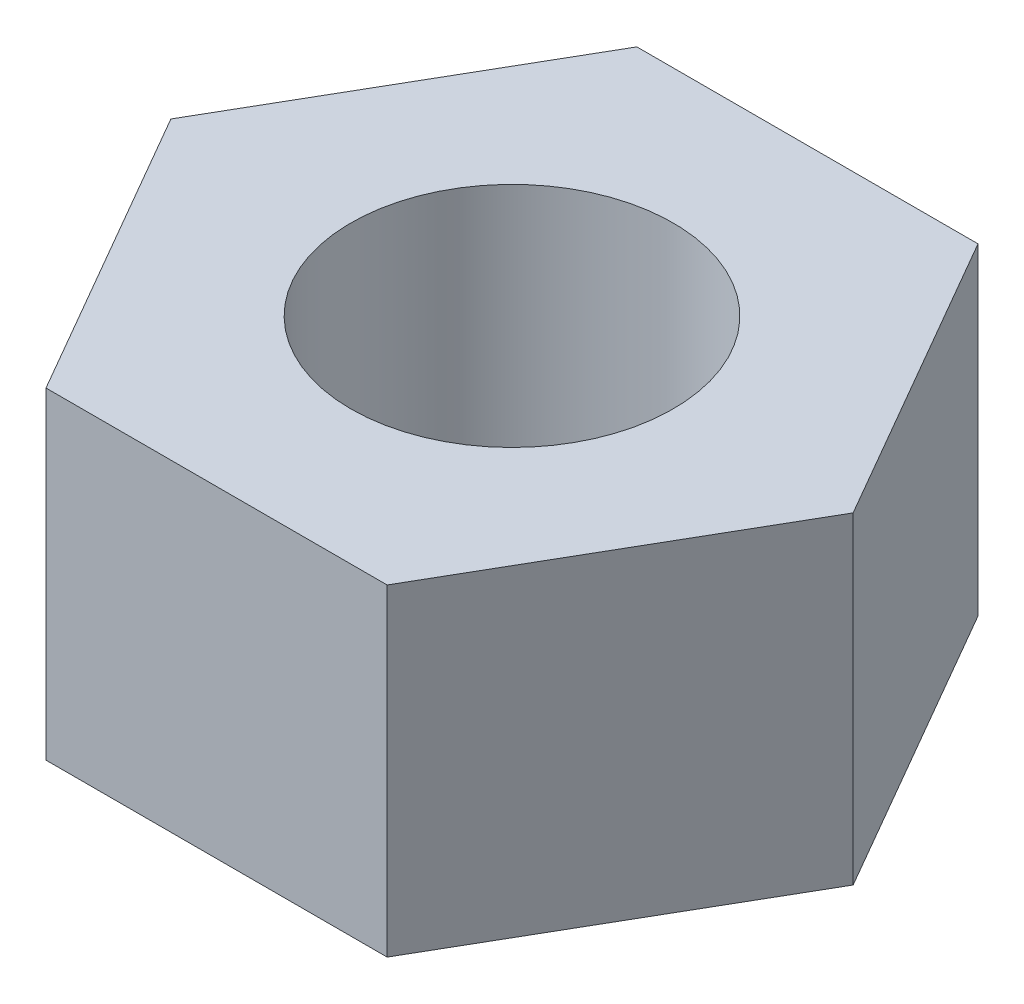
SolidWorks part; units mm, degrees
material "201 退火不锈钢 (SS)"
ref_plane "前视基准面" through (0, 0, 0) normal (0, 0, 1) x (1, 0, 0)
ref_plane "上视基准面" through (0, 0, 0) normal (0, 1, 0) x (1, 0, 0)
ref_plane "右视基准面" through (0, 0, 0) normal (1, 0, 0) x (0, 0, -1)
sketch "草图1" plane through (0, 0, 0) normal (0, 1, 0) x (1, 0, 0)
  line L1 (3.1754, 0) -> (1.5877, 2.75)
  line L2 (1.5877, 2.75) -> (-1.5877, 2.75)
  line L3 (-1.5877, 2.75) -> (-3.1754, 0)
  line L4 (-3.1754, 0) -> (-1.5877, -2.75)
  line L5 (-1.5877, -2.75) -> (1.5877, -2.75)
  line L6 (1.5877, -2.75) -> (3.1754, 0)
  circle A0 centre (0, 0) radius 1.5
  circle A1 centre (0, 0) radius 2.75 construction
  dimension "D2" = 3
  dimension "D1" = 5.5
extrude "凸台-拉伸1" add sketch "草图1" along normal blind 3
